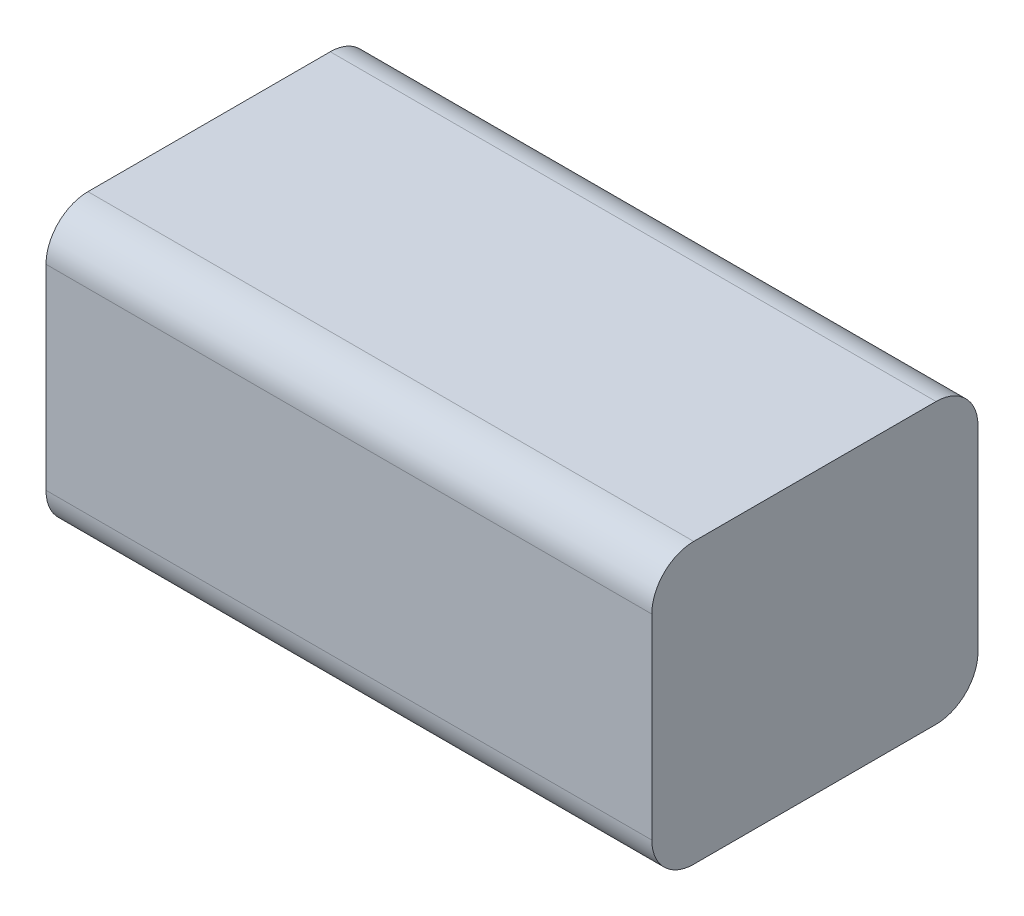
SolidWorks part; units mm, degrees
ref_plane "Front Plane" through (0, 0, 0) normal (0, 0, 1) x (1, 0, 0)
ref_plane "Top Plane" through (0, 0, 0) normal (0, 1, 0) x (1, 0, 0)
ref_plane "Right Plane" through (0, 0, 0) normal (1, 0, 0) x (0, 0, -1)
sketch "Sketch1" plane through (0, 0, 0) normal (0, 0, 1) x (1, 0, 0)
  line L0 (0, 0) -> (0, 30)
  line L1 (0, 30) -> (65, 30)
  line L2 (65, 30) -> (65, 0)
  line L3 (65, 0) -> (0, 0)
  dimension "D1" = 65
  dimension "D2" = 30
extrude "Boss-Extrude2" add sketch "Sketch1" along normal blind 35
fillet "Fillet2" radius 4.5 4 edges at (32.5, 0, 35) (32.5, 0, 0) (32.5, 30, 0) (32.5, 30, 35)
sketch "Sketch4" plane through (0, 30, 0) normal (0, 1, 0) x (1, 0, 0)
  line L0 (78.0862, 24.4054) -> (389.4195, 24.4054) construction
